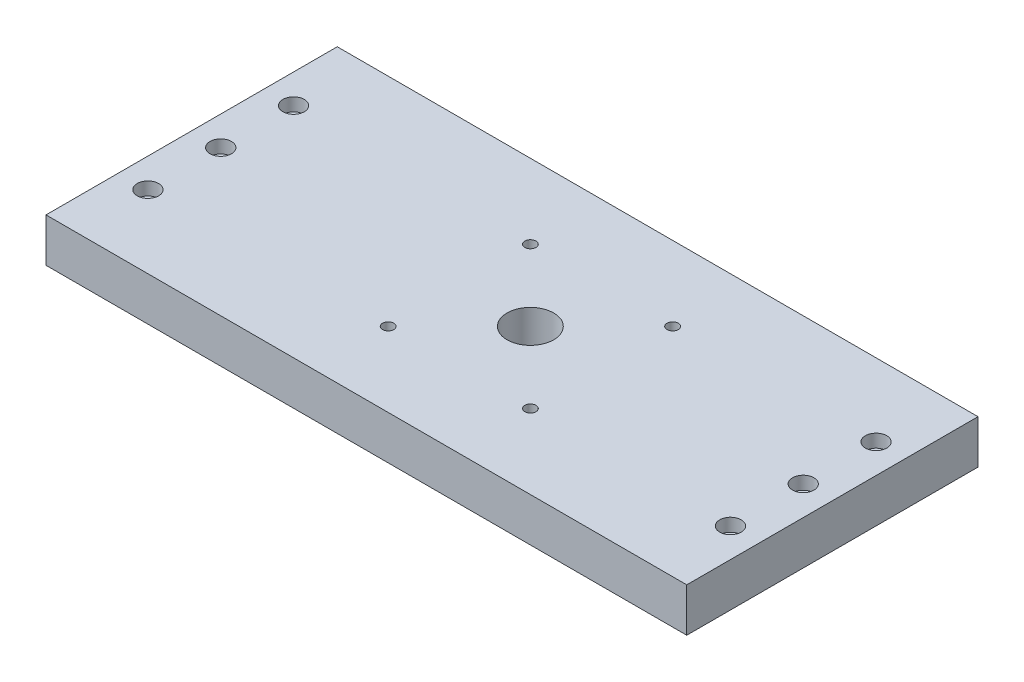
SolidWorks part; units mm, degrees
ref_plane "Front Plane" through (0, 0, 0) normal (0, 0, 1) x (1, 0, 0)
ref_plane "Top Plane" through (0, 0, 0) normal (0, 1, 0) x (1, 0, 0)
ref_plane "Right Plane" through (0, 0, 0) normal (1, 0, 0) x (0, 0, -1)
sketch "Sketch1" plane through (0, 0, 0) normal (0, 1, 0) x (1, 0, 0)
  line L1 (0, 0) -> (139.7, 0)
  line L2 (0, 0) -> (0, 63.5)
  line L3 (0, 63.5) -> (139.7, 63.5)
  line L4 (139.7, 0) -> (139.7, 63.5)
  line L5 (0, 0) -> (139.7, 63.5) construction
  line L6 (0, 63.5) -> (139.7, 0) construction
  point P4 (69.85, 31.75)
  dimension "D1" = 139.7
  dimension "D2" = 63.5
extrude "Boss-Extrude1" add sketch "Sketch1" along normal blind 9.525
sketch "Sketch2" plane through (0, 9.525, 0) normal (0, 1, 0) x (1, 0, 0)
  line L0 (69.85, 63.5) -> (69.85, 52.832) construction
  line L1 (139.7, 63.5) -> (0, 63.5) construction
  line L2 (69.85, 0) -> (69.85, 10.668) construction
  line L3 (0, 0) -> (139.7, 0) construction
  line L4 (69.85, 52.832) -> (69.85, 10.668) construction
  line L5 (48.768, 52.832) -> (48.768, 47.2567) construction
  line L6 (48.768, 10.668) -> (90.932, 10.668) construction
  line L7 (48.768, 10.668) -> (48.768, 52.832) construction
  line L8 (48.768, 52.832) -> (90.932, 52.832) construction
  line L9 (90.932, 10.668) -> (90.932, 52.832) construction
  line L10 (58.3489, 47.2567) -> (89.3623, 16.2433) construction
  line L11 (87.8403, 16.2433) -> (88.1794, 15.9481) construction
  line L12 (48.768, 47.2567) -> (58.3489, 47.2567) construction
  line L13 (58.3489, 10.668) -> (58.3489, 16.2433) construction
  line L14 (58.3489, 16.2433) -> (89.3623, 16.2433) construction
  line L15 (89.3623, 16.2433) -> (89.3623, 47.2567) construction
  line L16 (89.3623, 47.2567) -> (58.3489, 47.2567) construction
  line L20 (58.3489, 16.2433) -> (89.3623, 47.2567) construction
  circle A1 centre (58.3489, 47.2567) radius 1.2192
  circle A2 centre (89.3623, 47.2567) radius 1.2192
  circle A3 centre (89.3623, 16.2433) radius 1.2192
  circle A4 centre (58.3489, 16.2433) radius 1.2192
  circle A6 centre (73.8556, 31.75) radius 5.08
  point P8 (69.85, 31.75)
  dimension "D6" = 2.4384
  dimension "D7" = 2.4384
  dimension "D8" = 2.4384
  dimension "D9" = 2.4384
  dimension "D1" = 10.668
  dimension "D2" = 10.668
  dimension "D3" = 42.164
  dimension "D4" = 42.164
  dimension "D10" = 9.5809
extrude "Cut-Extrude1" cut sketch "Sketch2" against normal blind 9.525
sketch "Sketch3" plane through (0, 9.525, 0) normal (0, -1, 0) x (1, 0, 0)
  line L0 (0, 0) -> (139.7, 0) construction
  line L1 (139.7, -63.5) -> (127, -63.5) construction
  line L2 (139.7, -63.5) -> (139.7, 0) construction
  line L3 (139.7, 0) -> (127, 0) construction
  line L4 (127, -63.5) -> (127, 0) construction
  line L5 (139.7, -63.5) -> (127, 0) construction
  line L6 (139.7, 0) -> (127, -63.5) construction
  line L7 (6.35, -63.5) -> (6.35, -31.75) construction
  line L8 (0, -63.5) -> (12.7, -63.5) construction
  line L9 (0, -63.5) -> (0, 0) construction
  line L10 (0, 0) -> (12.7, 0) construction
  line L11 (12.7, -63.5) -> (12.7, 0) construction
  line L12 (0, -63.5) -> (12.7, 0) construction
  line L13 (0, 0) -> (12.7, -63.5) construction
  line L14 (6.35, -31.75) -> (6.35, 0) construction
  line L15 (133.35, -63.5) -> (133.35, -31.75) construction
  line L16 (133.35, -31.75) -> (133.35, 0) construction
  circle A0 centre (6.35, -15.875) radius 2.3368
  circle A1 centre (6.35, -31.75) radius 2.3368
  circle A2 centre (6.35, -47.625) radius 2.3368
  circle A3 centre (133.35, -47.625) radius 2.3368
  circle A4 centre (133.35, -31.75) radius 2.3368
  circle A5 centre (133.35, -15.875) radius 2.3368
  point P4 (133.35, -31.75)
  point P12 (6.35, -31.75)
  dimension "D3" = 4.6736
  dimension "D4" = 4.6736
  dimension "D5" = 4.6736
  dimension "D6" = 4.6736
  dimension "D7" = 4.6736
  dimension "D8" = 4.6736
  dimension "D1" = 12.7
  dimension "D2" = 12.7
extrude "Cut-Extrude3" cut sketch "Sketch3" along normal blind 2.8448
sketch "Sketch4" plane through (0, 9.525, 0) normal (0, 1, 0) x (1, 0, 0)
  circle A0 centre (6.35, 47.625) radius 1.2192
  circle A1 centre (6.35, 31.75) radius 1.2192
  circle A2 centre (6.35, 15.875) radius 1.2192
  circle A3 centre (133.35, 15.875) radius 1.2192
  circle A4 centre (133.35, 31.75) radius 1.2192
  circle A5 centre (133.35, 47.625) radius 1.2192
  dimension "D1" = 2.4384
  dimension "D2" = 2.4384
  dimension "D3" = 2.4384
  dimension "D4" = 2.4384
  dimension "D5" = 2.4384
  dimension "D6" = 2.4384
extrude "Cut-Extrude5" cut sketch "Sketch4" against normal through all
